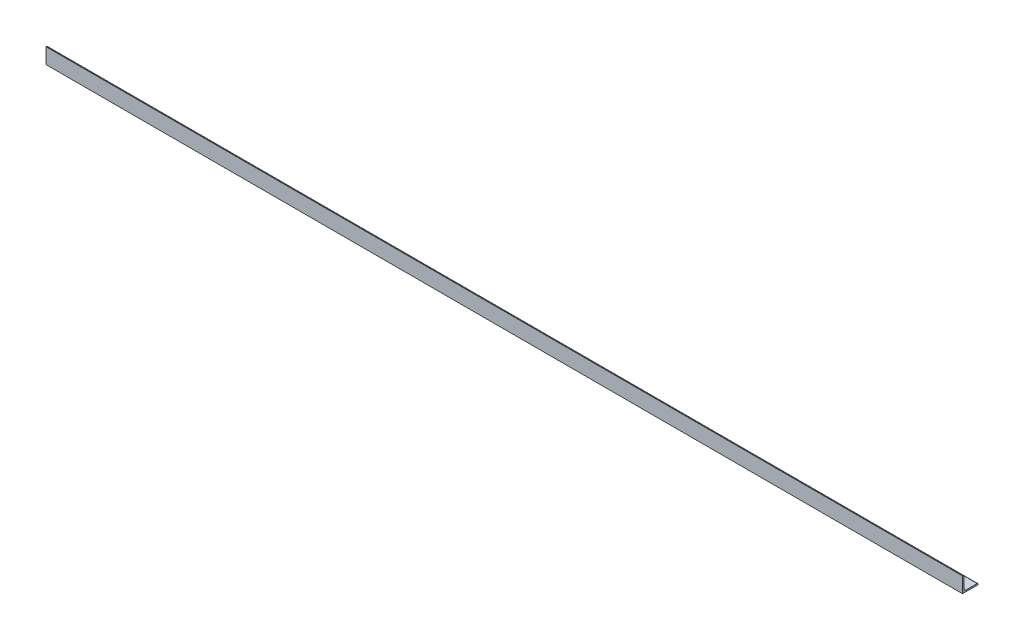
SolidWorks part; units mm, degrees
ref_plane "Front Plane" through (0, 0, 0) normal (0, 0, 1) x (1, 0, 0)
ref_plane "Top Plane" through (0, 0, 0) normal (0, 1, 0) x (1, 0, 0)
ref_plane "Right Plane" through (0, 0, 0) normal (1, 0, 0) x (0, 0, -1)
sketch "Sketch1" plane through (0, 0, 0) normal (1, 0, 0) x (0, 0, -1)
  line L0 (7.8565, 11.3361) -> (7.8565, -4.5389)
  line L1 (7.8565, -4.5389) -> (23.7315, -4.5389)
  line L2 (23.7315, -4.5389) -> (23.7315, -2.9387)
  line L3 (23.7315, -2.9387) -> (9.4567, -2.9387)
  line L4 (9.4567, -2.9387) -> (9.4567, 11.3361)
  line L5 (9.4567, 11.3361) -> (7.8565, 11.3361)
  dimension "D1" = 15.875
  dimension "D2" = 15.875
  dimension "D3" = 1.6002
  dimension "D4" = 1.6002
extrude "Boss-Extrude1" add sketch "Sketch1" along normal blind 939.8
sketch "Sketch2" plane through (0, -2.9387, 0) normal (0, 1, 0) x (1, 0, 0)
  line L0 (0, 23.7315) -> (0, 9.4567) construction
  line L1 (939.8, 23.7315) -> (0, 23.7315) construction
  line L2 (939.8, 23.7315) -> (939.8, 9.4567) construction
  circle A0 centre (12.7, 15.794) radius 3.556
  circle A1 centre (38.1, 15.794) radius 3.556
  circle A2 centre (927.1, 15.794) radius 3.556
  circle A3 centre (901.7, 15.794) radius 3.556
  dimension "D1" = 7.112
  dimension "D2" = 7.112
  dimension "D3" = 7.112
  dimension "D4" = 7.112
  dimension "D5" = 12.7
  dimension "D6" = 38.1
  dimension "D7" = 7.9375
  dimension "D8" = 7.9375
  dimension "D9" = 12.7
  dimension "D10" = 38.1
  dimension "D11" = 7.9375
  dimension "D12" = 7.9375
extrude "Cut-Extrude1" cut sketch "Sketch2" against normal through all
fillet "Fillet1" radius 1 2 edges at (469.9, 11.3361, -9.4567) (469.9, -2.9387, -23.7315)
fillet "Fillet2" radius 2 1 edges at (469.9, -2.9387, -9.4567)
sketch "Sketch4" plane through (0, -4.5389, 0) normal (0, -1, 0) x (1, 0, 0)
  circle A0 centre (469.9, -20.2332) radius 3.5687
extrude "Cut-Extrude2" cut sketch "Sketch4" against normal through all
